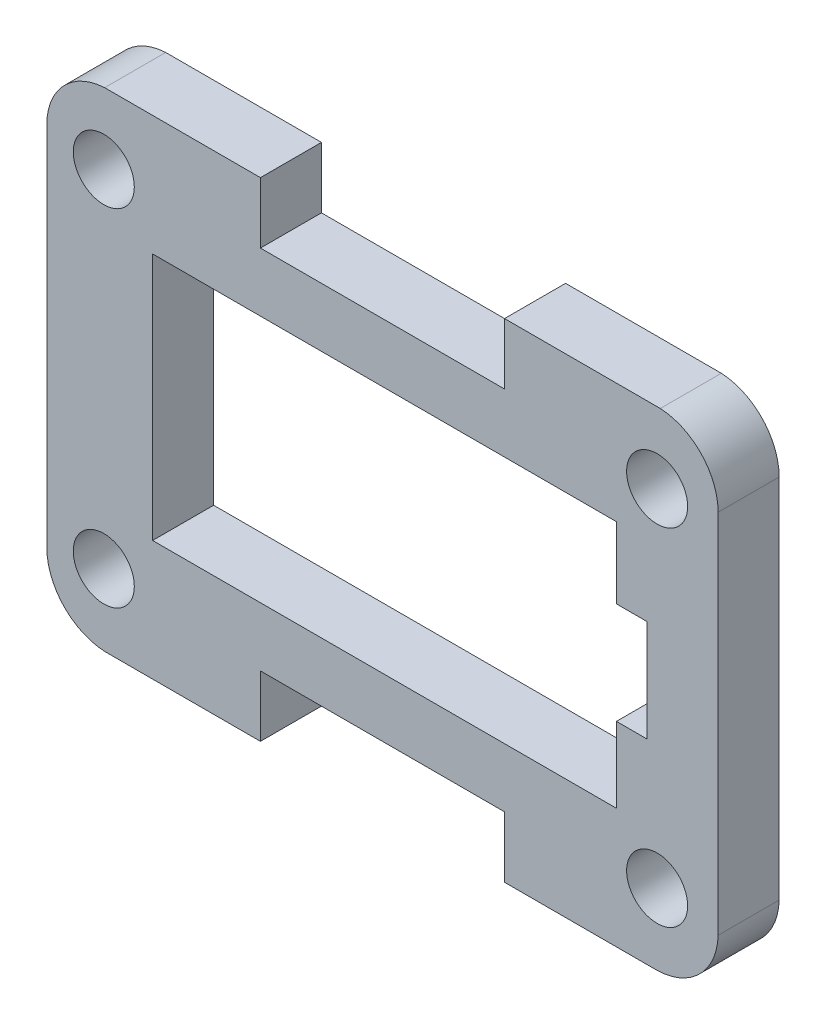
SolidWorks part; units mm, degrees
ref_plane "前基準面" through (0, 0, 0) normal (0, 0, 1) x (1, 0, 0)
ref_plane "上基準面" through (0, 0, 0) normal (0, 1, 0) x (1, 0, 0)
ref_plane "右基準面" through (0, 0, 0) normal (1, 0, 0) x (0, 0, -1)
sketch "草圖1" plane through (0, 0, 0) normal (0, 0, 1) x (1, 0, 0)
  line L0 (205.0001, 73.5885) -> (205.0001, 69.8885) construction
  line L1 (205.0001, 69.8885) -> (182.2001, 69.8885) construction
  line L2 (206.5001, 73.5885) -> (205.0001, 73.5885) construction
  line L3 (206.5001, 78.5885) -> (206.5001, 73.5885) construction
  line L4 (205.0001, 78.5885) -> (206.5001, 78.5885) construction
  line L5 (205.0001, 82.0885) -> (205.0001, 78.5885) construction
  line L6 (182.2001, 82.0885) -> (205.0001, 82.0885) construction
  line L7 (182.2001, 69.8885) -> (182.2001, 82.0885) construction
  line L8 (199.5001, 87.9863) -> (199.5001, 84.9865) construction
  line L9 (187.5001, 84.9865) -> (187.5001, 87.9863) construction
  line L10 (187.5001, 87.9863) -> (179.8429, 87.9863) construction
  line L11 (199.5001, 84.9865) -> (187.5001, 84.9865) construction
  line L12 (199.5001, 63.9865) -> (199.5001, 66.9865) construction
  line L13 (199.5001, 66.9865) -> (187.5001, 66.9865) construction
  line L14 (187.5001, 66.9865) -> (187.5001, 63.9865) construction
  line L15 (205.0001, 73.5885) -> (205.0001, 69.8885)
  line L16 (205.0001, 69.8885) -> (182.2001, 69.8885)
  line L17 (206.5001, 73.5885) -> (205.0001, 73.5885)
  line L18 (206.5001, 78.5885) -> (206.5001, 73.5885)
  line L19 (205.0001, 78.5885) -> (206.5001, 78.5885)
  line L20 (205.0001, 82.0885) -> (205.0001, 78.5885)
  line L21 (182.2001, 82.0885) -> (205.0001, 82.0885)
  line L22 (182.2001, 69.8885) -> (182.2001, 82.0885)
  line L23 (199.5001, 87.9863) -> (199.5001, 84.9865)
  line L24 (187.5001, 84.9865) -> (187.5001, 87.9863)
  line L25 (187.5001, 87.9863) -> (179.8429, 87.9863)
  line L26 (199.5001, 84.9865) -> (187.5001, 84.9865)
  line L27 (199.5001, 63.9865) -> (199.5001, 66.9865)
  line L28 (199.5001, 66.9865) -> (187.5001, 66.9865)
  line L29 (187.5001, 66.9865) -> (187.5001, 63.9865)
  line L30 (199.5001, 87.9863) -> (207.1573, 87.9863)
  line L31 (210.0001, 84.9905) -> (210.0001, 66.9823)
  line L32 (187.5001, 63.9865) -> (179.8429, 63.9865)
  line L33 (199.5001, 63.9865) -> (207.0001, 63.9865)
  line L34 (177.0001, 66.9823) -> (177.0001, 84.9905)
  circle A0 centre (179.8, 67.4865) radius 1.5 construction
  circle A1 centre (179.8001, 84.4866) radius 1.5 construction
  circle A2 centre (207.0001, 84.4865) radius 1.5 construction
  circle A3 centre (207.0001, 67.4865) radius 1.5 construction
  arc A4 (177.0001, 66.9823) -> (179.8429, 63.9865) centre (180, 66.9823) ccw construction
  arc A5 (207.0001, 63.9865) -> (210.0001, 66.9823) centre (206.9216, 67.0651) ccw construction
  arc A6 (210.0001, 84.9905) -> (207.1573, 87.9863) centre (207.0002, 84.9906) ccw construction
  arc A7 (179.8429, 87.9863) -> (177.0001, 84.9905) centre (180, 84.9906) ccw construction
  circle A8 centre (179.8, 67.4865) radius 1.5
  circle A9 centre (179.8001, 84.4866) radius 1.5
  circle A10 centre (207.0001, 84.4865) radius 1.5
  circle A11 centre (207.0001, 67.4865) radius 1.5
  arc A12 (177.0001, 66.9823) -> (179.8429, 63.9865) centre (180, 66.9823) ccw
  arc A13 (207.0001, 63.9865) -> (210.0001, 66.9823) centre (206.9216, 67.0651) ccw
  arc A14 (210.0001, 84.9905) -> (207.1573, 87.9863) centre (207.0002, 84.9906) ccw
  arc A15 (179.8429, 87.9863) -> (177.0001, 84.9905) centre (180, 84.9906) ccw
extrude "填料-伸長1" add sketch "草圖1" along normal blind 3
